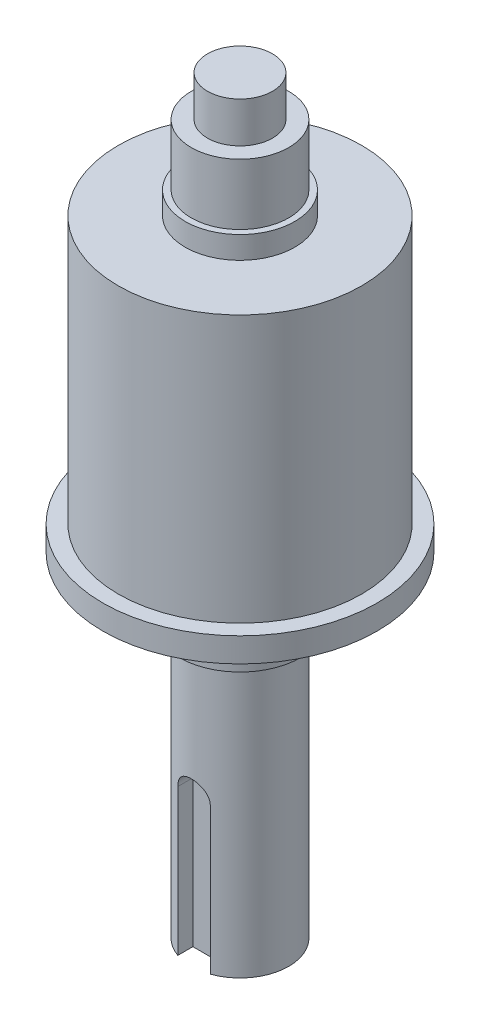
SolidWorks part; units mm, degrees
material "AISI 1035 Steel (SS)"
ref_plane "Front Plane" through (0, 0, 0) normal (0, 0, 1) x (1, 0, 0)
ref_plane "Top Plane" through (0, 0, 0) normal (0, 1, 0) x (1, 0, 0)
ref_plane "Right Plane" through (0, 0, 0) normal (1, 0, 0) x (0, 0, -1)
sketch "Sketch2" plane through (0, 0, 0) normal (0, 0, 1) x (1, 0, 0)
  line L0 (0, 40.0334) -> (0, -27.2464) construction
  line L11 (0, 0) -> (-4, 0)
  line L12 (-4, 0) -> (-4, -5)
  line L13 (-4, -5) -> (-6, -5)
  line L14 (-6, -5) -> (-6, -12.5)
  line L15 (-6, -12.5) -> (-6.75, -12.5)
  line L16 (-6.75, -12.5) -> (-6.75, -15.25)
  line L17 (-6.75, -15.25) -> (-14.9815, -15.25)
  line L18 (-14.9815, -15.25) -> (-14.9815, -48.11)
  line L26 (0, -92.285) -> (0, 0)
  line L28 (-16.8815, -51.11) -> (-16.8815, -48.11)
  line L29 (-16.8815, -48.11) -> (-14.9815, -48.11)
  line L30 (-16.8815, -51.11) -> (-8.25, -51.11)
  line L31 (-8.25, -51.11) -> (-8.25, -53.61)
  line L32 (-14.9815, -48.11) -> (-14.9815, -51.11) construction
  line L33 (-8.25, -53.61) -> (-7.5, -53.61)
  line L34 (-7.5, -53.61) -> (-7.5, -58.61)
  line L35 (-7.5, -58.61) -> (-6, -58.61)
  line L36 (-6, -58.61) -> (-6, -92.285)
  line L37 (-6, -92.285) -> (0, -92.285)
  dimension "D1" = 4
  dimension "D2" = 5
  dimension "D3" = 6
  dimension "D4" = 7.5
  dimension "D5" = 6.75
  dimension "D6" = 2.75
  dimension "D7" = 14.9815
  dimension "D8" = 32.86
  dimension "D10" = 3
  dimension "D11" = 8.25
  dimension "D12" = 2.5
  dimension "D13" = 7.5
  dimension "D14" = 5
  dimension "D15" = 6
  dimension "D16" = 33.675
  dimension "D9" = 1.9
revolve "Revolve1" add sketch "Sketch2" angle 360 about L0
sketch "Sketch3" plane through (0, -92.285, 0) normal (0, -1, 0) x (1, 0, 0)
  line L4 (-2, 5.6569) -> (-2, 7.8) construction
  line L5 (-2, 7.8) -> (2, 7.8) construction
  line L6 (2, 7.8) -> (2, 5.6569) construction
  line L7 (0, -6) -> (12.9978, -6) construction
  line L8 (-2, 5.6569) -> (-2, 3.8)
  line L9 (-2, 3.8) -> (2, 3.8)
  line L10 (2, 3.8) -> (2, 5.6569)
  circle A1 centre (0, 0) radius 6
  arc A2 (2, 5.6569) -> (-2, 5.6569) centre (0, 0) ccw
  point P2 (0, 7.8)
  dimension "D2" = 4
  dimension "D3" = 13.8
  dimension "D4" = 4
extrude "Cut-Extrude1" cut sketch "Sketch3" against normal blind 15
sketch "Sketch4" plane through (0, 0, 3.8) normal (0, 0, 1) x (1, 0, 0)
  line L0 (-2, -77.285) -> (-2, -74.285)
  line L1 (2, -74.285) -> (2, -77.285)
  line L2 (-4.5886, -72.285) -> (3.957, -72.285) construction
  line L3 (-2, -92.285) -> (2, -92.285) construction
  line L4 (-2, -77.285) -> (-2, -92.285)
  line L5 (-2, -92.285) -> (2, -92.285)
  line L6 (2, -92.285) -> (2, -77.285)
  arc A0 (-2, -74.285) -> (2, -74.285) centre (0, -74.285) cw
  dimension "D1" = 20
extrude "Cut-Extrude2" cut sketch "Sketch4" along normal through all
equation "\"Stator_OD\"= 60'No Tolerance given"
equation "\"A\"=35.81 'taken off spec sheet for 06808 (A)"
equation "\"Rotor_ID\"= 30'No Tolerance Given"
equation "\"back_bearing_Thickness\"= 5'-0.12"
equation "\"back_bearing_OD\"= 24'-0.009 https://www.mcmaster.com/5972K155/"
equation "\"Stator_Gap\"= 0.0375'+- 0.0125 (From 1.3.3.1 Kollmorgen manual)"
equation "\"Back_mount_hole\"= 1.75'To be tapped to M2 (USE LOCKTITE)"
equation "\"facePlate_Mount_Hole\"= 2.75'To be tapped to M3"
equation "\"final_shaftD\"= 12'To fit in harmonic"
equation "\"back_bearing_ID\"= 15'"
equation "\"rotor_shaftD\"= \"Rotor_ID\" - (\"rotor-shaft_gap\")*2'"
equation "\"back_bearing_IDOD\"= 16.5'measured off CAD, actually 16.75, but rounded down to nicer number"
equation "\"final_shaftL\"= 5.25+3+\"sheet_thick\"+\"connector_thick\"-3+\"harmon_coupleL\"+0.5-\"shaft_Ladjust\"'length to make everything nice and aligned"
equation "\"D1@Sketch2\"=4"
equation "\"D3@Sketch2\"=\"front_bearing_ID\"/2"
equation "\"D4@Sketch2\" = \"front_bearing_Thickness\" + 2.5"
equation "\"D5@Sketch2\"=\"front_bearing_IDOD\" / 2"
equation "\"D8@Sketch2\"=\"rotor_height\""
equation "\"front_bearing_ID\"= 12'https://www.mcmaster.com/5972K154/"
equation "\"front_bearing_OD\"= 21'-0.009"
equation "\"front_bearing_IDOD\"= 13.5'Measured off CAD. Actually 13.75, but rounded down"
equation "\"front_bearing_Thickness\"= 5'-0.12"
equation "\"rotor_thickness\"= 2.4'measured off CAD"
equation "\"rotor_height\"= 32.86'+-0.075 taken off spec sheet for 06826 (C)"
equation "\"D11@Sketch2\"=\"back_bearing_IDOD\"/2"
equation "\"D13@Sketch2\"=\"back_bearing_ID\"/2"
equation "\"D14@Sketch2\"=\"back_bearing_Thickness\""
equation "\"D15@Sketch2\"=\"final_shaftD\"/2"
equation "\"D16@Sketch2\"=\"final_shaftL\""
equation "\"D9@Sketch2\"=\"rotor_thickness\"-0.5"
equation "\"rotor-shaft_gap\" = 0.0185 '+-0.0065 (from manual)"
equation "\"D7@Sketch2\"=\"Rotor_ID\"/2-\"rotor-shaft_gap\""
equation "\"B\"= 26.3'+-0.35 taken off spec sheet for 06826"
equation "\"key_L\"= 20'-0.2 https://www.mcmaster.com/2977N19/"
equation "\"key_H\"= 4'-0.03"
equation "\"key_W\"= 4'-0.03"
equation "\"harmon_keyH\"= 13.8'+0.1 from drawing"
equation "\"harmon_coupleL\"= 21.5' taken from drawing https://www.harmonicdrive.net/_hd/content/caddownloads/dxf/csf-2uh-ulw_gearheads/CSF-17-xxx-2UH-ULW.pdf"
equation "\"D2@Sketch3\"=\"key_W\""
equation "\"D3@Sketch3\"=\"harmon_keyH\""
equation "\"D4@Sketch3\"=\"key_H\""
equation "\"D1@Cut-Extrude1\"=\"key_L\"-5"
equation "\"D1@Sketch4\"=\"key_L\""
equation "\"harmon_diam\"= 81' from drawing"
equation "\"harmon_BCD\"= 74.5' from drawing"
equation "\"harmon_holeD1\"= 3.4' from drawing"
equation "\"harmon_holeD2\"= 3' from drawing"
equation "\"harmon_holeAng\"= 18' from drawing"
equation "\"sheet_thick\"= 1/8*25.4 'random, replace w actual sheet thickness when u feel like :)"
equation "\"nut-thickness\"= 5 'idk measure the ones in the shop and adjust"
equation "\"connector_thick\"= 10' random for now"
equation "\"shaft_Ladjust\"= 6.75' sorry. It's silly, but it works."
